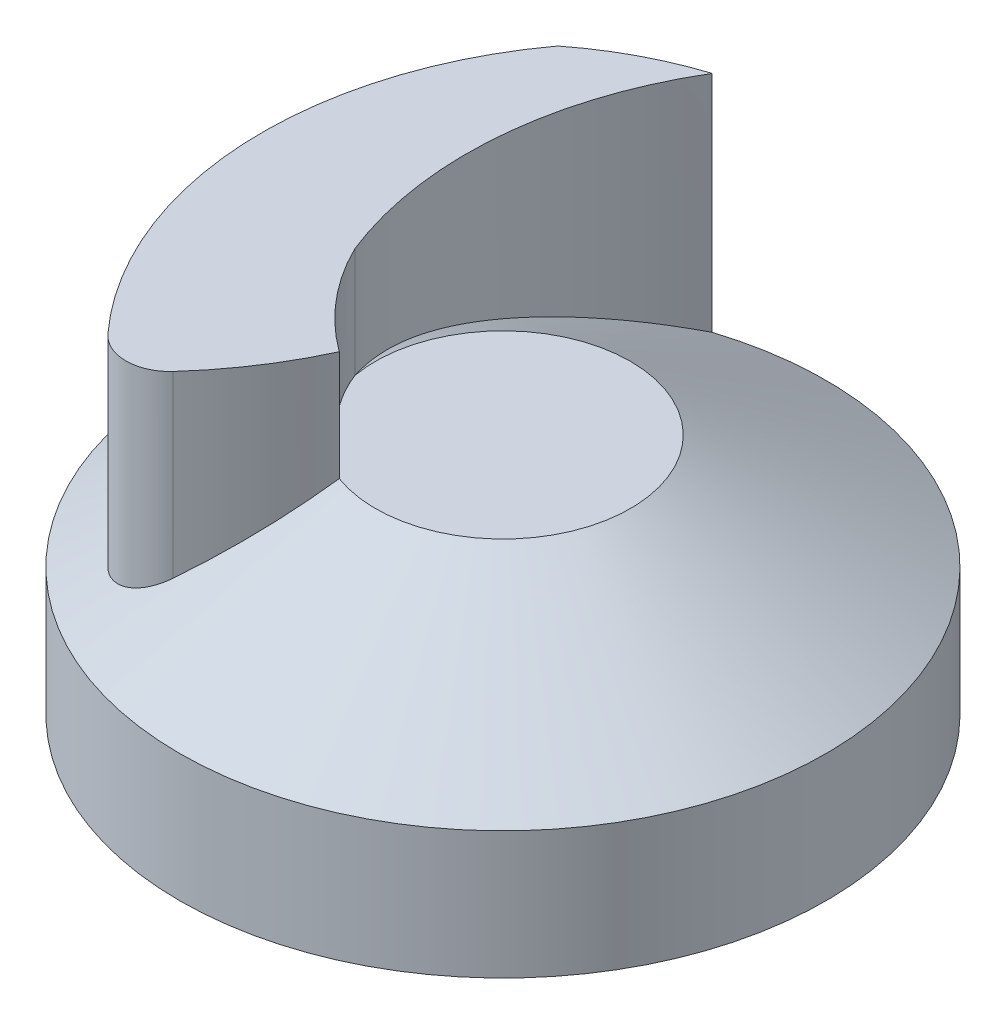
SolidWorks part; units mm, degrees
material "Сталь 3 ГОСТ 535-88"
ref_plane "Спереди" through (0, 0, 0) normal (0, 0, 1) x (1, 0, 0)
ref_plane "Сверху" through (0, 0, 0) normal (0, 1, 0) x (1, 0, 0)
ref_plane "Справа" through (0, 0, 0) normal (1, 0, 0) x (0, 0, -1)
sketch "Эскиз1" plane through (0, 0, 0) normal (0, 0, 1) x (1, 0, 0)
  line L0 (0, 0) -> (0, -40.7027) construction
  line L1 (0, 0) -> (-73.5, 0)
  line L2 (-73.5, 0) -> (-73.5, 29)
  line L3 (-73.5, 29) -> (-29, 55)
  line L4 (-29, 55) -> (0, 55)
  line L5 (0, 55) -> (0, 0)
  dimension "D1" = 147
  dimension "D2" = 58
  dimension "D3" = 29
  dimension "D4" = 55
revolve "Повернуть1" add sketch "Эскиз1" angle 360 about L0
ref_plane "Плоскость1" through (0, 80, 0) normal (0, 1, 0) x (1, 0, 0)
sketch "Эскиз2" plane through (0, 80, 0) normal (0, -1, 0) x (-1, 0, 0)
  line L0 (0, 0) -> (0, -103.2253) construction
  line L1 (0, 0) -> (73.5, 0) construction
  circle A0 centre (0, 0) radius 73.5 construction
  arc A1 (39.8269, -50.019) -> (45.3803, 57.8177) centre (-23.3204, 7.2943) ccw
  arc A3 (10, -27.2213) -> (25, -50) centre (91.7984, 10.3156) ccw
  circle A4 centre (0, 0) radius 29 construction
  arc A5 (10, -27.2213) -> (28.5497, -5.0907) centre (-25.3572, 21.2542) ccw
  arc A6 (28.5497, -5.0907) -> (22.4109, 70) centre (-50.463, 26.2462) ccw
  arc A7 (39.8269, -50.019) -> (25, -50) centre (32.422, -43.2983) cw
  arc A8 (45.3803, 57.8177) -> (22.4109, 70) centre (0, 0) ccw
  point P5 (28.5497, -5.0907)
  point P6 (0, 0)
  point P12 (55.7553, 26.6741)
  point P16 (48.3825, -15.9141)
  point P17 (0, 0)
  point P20 (10, -27.2213)
  point P22 (0, 0)
  point P25 (45.3803, 14.1205)
  point P26 (52.6318, 38.9168)
  point P28 (45.3803, 56.177)
  dimension "D1" = 20
  dimension "D2" = 10
  dimension "D4" = 90
  dimension "D6" = 26
  dimension "D9" = 85
  dimension "D3" = 50
  dimension "D8" = 70
  dimension "D10" = 50
extrude "Бобышка-Вытянуть1" add sketch "Эскиз2" along normal up to surface (25 mm away)
chamfer "Фаска1" [suppressed] distance 16 angle 60
